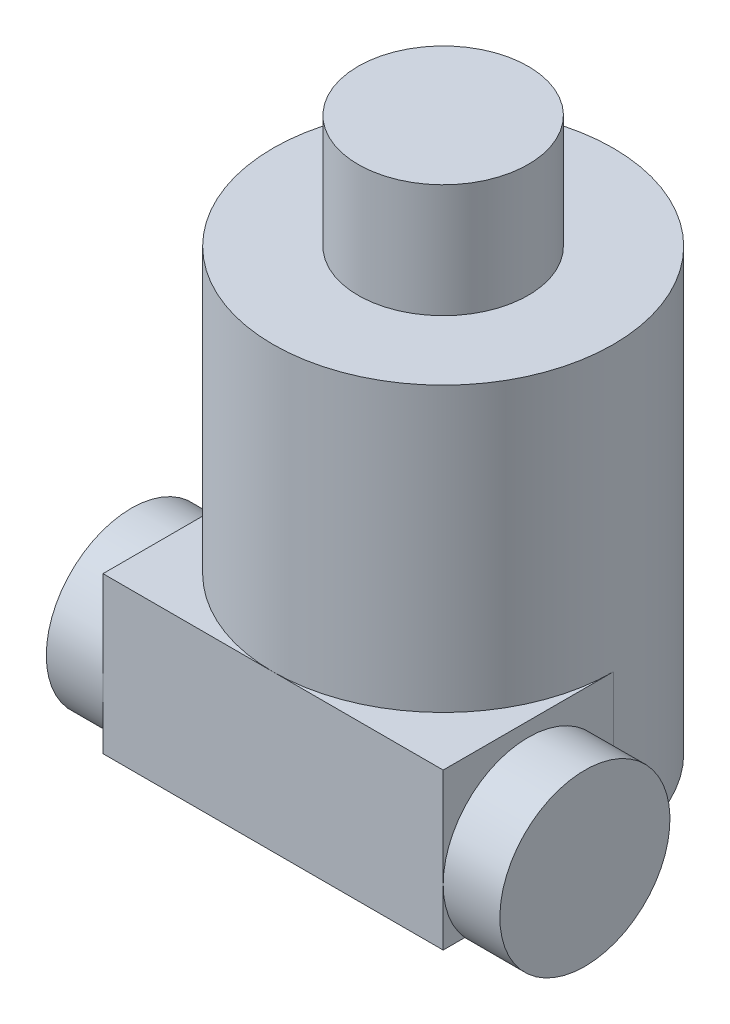
SolidWorks part; units mm, degrees
ref_plane "Plan de face" through (0, 0, 0) normal (0, 0, 1) x (1, 0, 0)
ref_plane "Plan de dessus" through (0, 0, 0) normal (0, 1, 0) x (1, 0, 0)
ref_plane "Plan de droite" through (0, 0, 0) normal (1, 0, 0) x (0, 0, -1)
sketch "Esquisse1" plane through (0, 0, 0) normal (0, 0, 1) x (1, 0, 0)
  line L0 (0, 0) -> (-60, 0)
  line L1 (-60, 0) -> (-60, 155)
  line L2 (-60, 155) -> (-30, 155)
  line L3 (-30, 155) -> (-30, 195)
  line L4 (-30, 195) -> (0, 195)
  line L5 (0, 195) -> (0, 0)
  dimension "D1" = 60
  dimension "D2" = 30
  dimension "D3" = 155
  dimension "D4" = 195
revolve "Révolution1" add sketch "Esquisse1" angle 360 about L5
sketch "Esquisse2" plane through (0, 0, 0) normal (0, -1, 0) x (1, 0, 0)
  line L1 (-60, 0) -> (60, 0)
  line L2 (-60, 0) -> (-60, 60)
  line L3 (-60, 60) -> (60, 60)
  line L4 (60, 0) -> (60, 60)
  circle A0 centre (0, 0) radius 60 construction
  dimension "D1" = 60
  dimension "D2" = 120
  dimension "D3" = 60
extrude "Boss.-Extru.1" add sketch "Esquisse2" against normal blind 55
sketch "Esquisse3" plane through (-60, 0, 0) normal (-1, 0, 0) x (0, 0, 1)
  line L0 (60, 0) -> (0, 0) construction
  line L1 (60, 55) -> (60, 0) construction
  circle A0 centre (30, 20) radius 30
  point P6 (60, 27.5)
  dimension "D1" = 60
  dimension "D2" = 20
  dimension "D3" = 30
extrude "Boss.-Extru.2" add sketch "Esquisse3" along normal blind 20
mirror "Symétrie1" about plane through (0, 0, 0) normal (1, 0, 0) of "Boss.-Extru.2"
